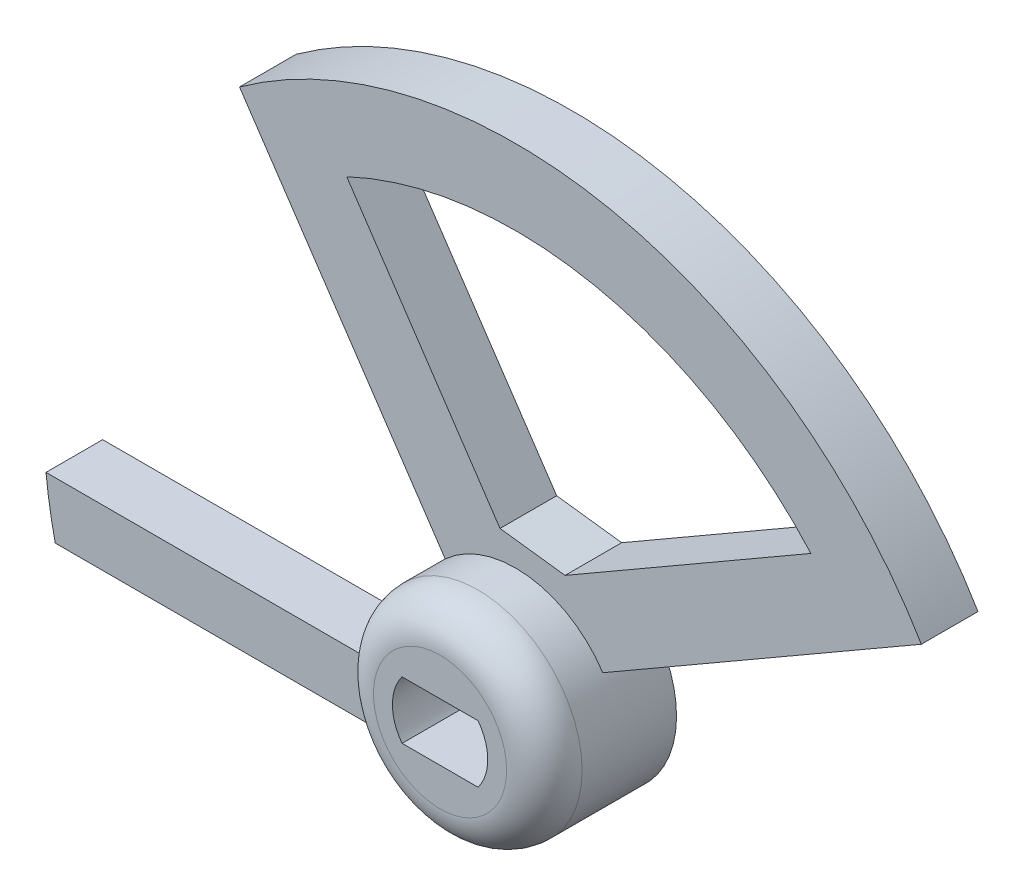
SolidWorks part; units mm, degrees
ref_plane "Front Plane" through (0, 0, 0) normal (0, 0, 1) x (1, 0, 0)
ref_plane "Top Plane" through (0, 0, 0) normal (0, 1, 0) x (1, 0, 0)
ref_plane "Right Plane" through (0, 0, 0) normal (1, 0, 0) x (0, 0, -1)
sketch "Sketch1" plane through (0, 0, 0) normal (0, 0, 1) x (1, 0, 0)
  line L1 (2.0125, -1.525) -> (-2.0125, -1.525)
  line L2 (2.0125, -1.525) -> (2.0125, 1.525)
  line L3 (2.0125, 1.525) -> (-2.0125, 1.525)
  line L4 (-2.0125, -1.525) -> (-2.0125, 1.525)
  line L5 (2.0125, -1.525) -> (-2.0125, 1.525) construction
  line L6 (2.0125, 1.525) -> (-2.0125, -1.525) construction
  line L14 (-9.708, 0) -> (10.4475, 0) construction
  line L15 (-2.0125, 1.525) -> (-14.6228, 20.2774)
  line L16 (0, -2.525) -> (-25, -2.525)
  line L17 (0, -2.525) -> (0, -5.525)
  line L18 (0, -5.525) -> (-25, -5.525)
  line L19 (-25, -2.525) -> (-25, -5.525)
  line L20 (2.0125, 0) -> (25, 0)
  line L21 (-14.6228, 20.2774) -> (-24.8722, -2.525)
  line L22 (2.0125, 1.525) -> (21.4917, 12.7713)
  circle A0 centre (0, 0) radius 2.525
  circle A1 centre (0, 0) radius 5.525
  circle A2 centre (0, 0) radius 25
  dimension "D2" = 5.05
  dimension "D3" = 3
  dimension "D5" = 50
  dimension "D1" = 3.05
  dimension "D4" = 25
  dimension "D6" = 25
  dimension "D7" = 30
extrude "Boss-Extrude2" add sketch "Sketch1" along normal blind 3 contours L16 A2 L18 A1 | L1 A0 | L3 A0 | L22 A1 L15 A0 | L15 A1 L16 A0 | L16 A1 L17 | L17 A1 L20 A0 | L20 A1 L22 A0 | L22 A2 L15 A1
sketch "Sketch2" plane through (0, 0, 3) normal (0, 0, 1) x (1, 0, 0)
  line L0 (4.6198, 3.0304) -> (21.4917, 12.7713) construction
  line L1 (-3.7287, 4.0771) -> (-14.6228, 20.2774) construction
  line L2 (4.6198, 3.0304) -> (21.4917, 12.7713)
  line L3 (-3.7287, 4.0771) -> (-14.6228, 20.2774)
  line L4 (-0.4094, 6.3092) -> (-8.9437, 19.0003)
  line L5 (2.6198, 6.4945) -> (15.6413, 14.0124)
  line L6 (-3.7287, 4.0771) -> (4.6198, 3.0304)
  line L7 (2.6198, 6.4945) -> (-0.8243, 6.9263)
  arc A0 (21.4917, 12.7713) -> (-14.6228, 20.2774) centre (0, 0) ccw construction
  arc A1 (21.4917, 12.7713) -> (-14.6228, 20.2774) centre (0, 0) ccw
  arc A2 (15.6413, 14.0124) -> (-8.9437, 19.0003) centre (0, 0) ccw
  dimension "D1" = 4
extrude "Cut-Extrude1" cut sketch "Sketch2" against normal blind 3 contours L5 A2 L4 L7
sketch "Sketch3" plane through (0, 0, 3) normal (0, 0, 1) x (1, 0, 0)
  line L0 (2.0125, 1.525) -> (-2.0125, 1.525) construction
  line L1 (2.0125, -1.525) -> (-2.0125, -1.525) construction
  line L2 (2.0125, 1.525) -> (-2.0125, 1.525)
  line L3 (2.0125, -1.525) -> (-2.0125, -1.525)
  line L4 (4.6198, 3.0304) -> (21.4917, 12.7713)
  line L5 (-14.6228, 20.2774) -> (-3.7287, 4.0771)
  line L6 (-4.9143, -2.525) -> (-24.8722, -2.525)
  line L7 (-24.3818, -5.525) -> (0, -5.525)
  line L8 (4.6198, 3.0304) -> (21.4917, 12.7713)
  line L9 (-14.6228, 20.2774) -> (-3.7287, 4.0771)
  line L10 (-4.9143, -2.525) -> (-24.8722, -2.525)
  line L11 (-24.3818, -5.525) -> (0, -5.525)
  circle A0 centre (0, 0) radius 5.525
  arc A1 (-2.0125, 1.525) -> (-2.0125, -1.525) centre (0, 0) ccw construction
  arc A2 (2.0125, -1.525) -> (2.0125, 1.525) centre (0, 0) ccw construction
  arc A3 (-2.0125, 1.525) -> (-2.0125, -1.525) centre (0, 0) ccw
  arc A4 (0, -5.525) -> (4.6198, 3.0304) centre (0, 0) ccw
  arc A5 (21.4917, 12.7713) -> (-14.6228, 20.2774) centre (0, 0) ccw
  arc A6 (-3.7287, 4.0771) -> (-4.9143, -2.525) centre (0, 0) ccw
  arc A7 (-24.8722, -2.525) -> (-24.3818, -5.525) centre (0, 0) ccw
  arc A8 (0, -5.525) -> (4.6198, 3.0304) centre (0, 0) ccw
  arc A9 (21.4917, 12.7713) -> (-14.6228, 20.2774) centre (0, 0) ccw
  arc A10 (-3.7287, 4.0771) -> (-4.9143, -2.525) centre (0, 0) ccw
  arc A11 (-24.8722, -2.525) -> (-24.3818, -5.525) centre (0, 0) ccw
  arc A12 (2.0125, -1.525) -> (2.0125, 1.525) centre (0, 0) ccw
  arc M13 (0, -5.525) -> (4.6198, 3.0304) centre (0, 0) ccw
  arc M17 (-3.7287, 4.0771) -> (-4.9143, -2.525) centre (0, 0) ccw
  arc M21 (-2.0125, -1.525) -> (-2.0125, 1.525) centre (0, 0) cw
  line M22 (-2.0125, 1.525) -> (2.0125, 1.525)
  arc M23 (2.0125, 1.525) -> (2.0125, -1.525) centre (0, 0) cw
  line M24 (2.0125, -1.525) -> (-2.0125, -1.525)
  dimension "D1" = 0
extrude "Boss-Extrude3" add sketch "Sketch3" along normal blind 4 contours A0 M13 M17 M24 M21 M22 M23
fillet "Fillet1" radius 2 1 edges at (5.525, 0, 7)
